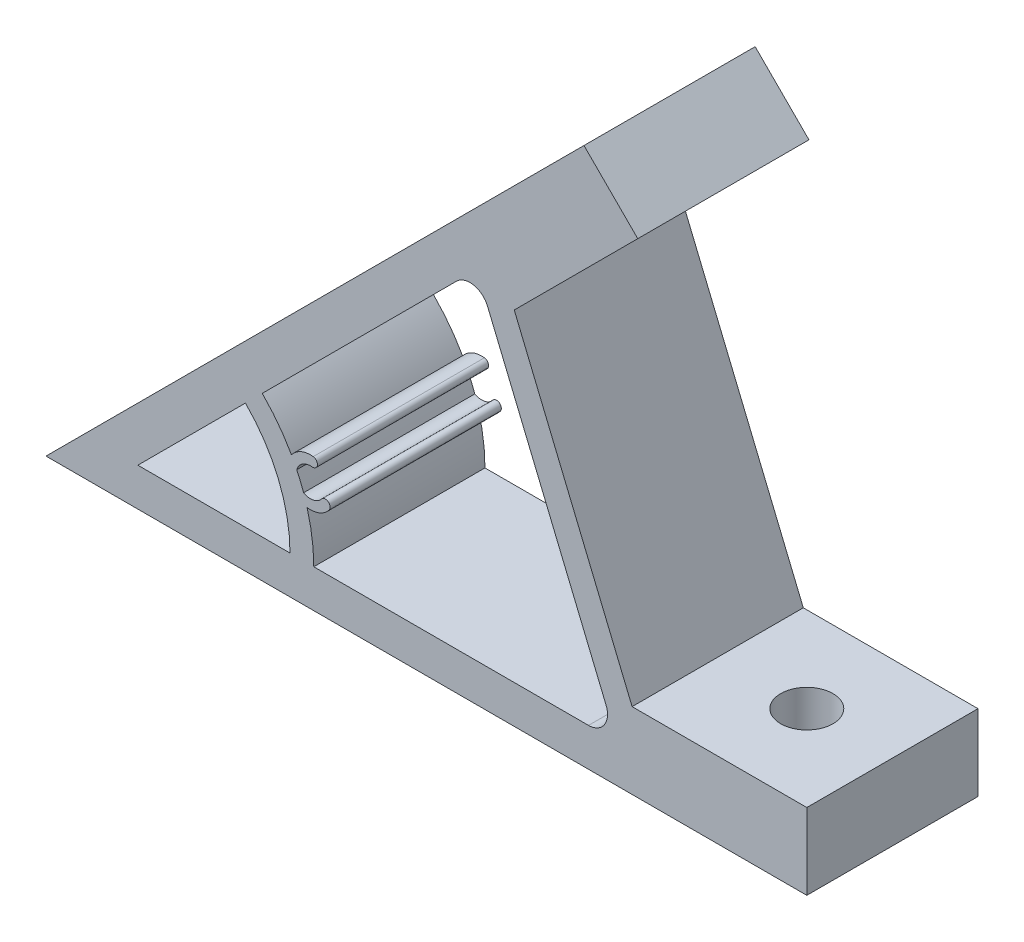
SolidWorks part; units mm, degrees
ref_plane "前视基准面" through (0, 0, 0) normal (0, 0, 1) x (1, 0, 0)
ref_plane "上视基准面" through (0, 0, 0) normal (0, 1, 0) x (1, 0, 0)
ref_plane "右视基准面" through (0, 0, 0) normal (1, 0, 0) x (0, 0, -1)
sketch "草图1" plane through (0, 0, 0) normal (0, 0, 1) x (1, 0, 0)
  line L0 (0, 0) -> (97.3951, 0) construction
  line L1 (0, 0) -> (65.6523, 65.6523) construction
  line L2 (0, 0) -> (80, 0)
  line L3 (0, 0) -> (56.5685, 56.5685)
  line L4 (80, 0) -> (80, 8)
  line L5 (49.2357, 37.922) -> (61.6298, 8)
  line L6 (56.5685, 56.5685) -> (62.2254, 50.9117)
  line L7 (62.2254, 50.9117) -> (49.2357, 37.922)
  line L8 (58.894, 6.7654) -> (46.4282, 36.8605)
  line L9 (43.1662, 37.5094) -> (9.6569, 4)
  line L10 (9.6569, 4) -> (57.0463, 4)
  line L11 (0, 0) -> (69.2985, 28.7044) construction
  line L12 (80, 8) -> (61.6298, 8)
  arc A0 (57.0463, 4) -> (58.894, 6.7654) centre (57.0463, 6) ccw
  arc A1 (46.4282, 36.8605) -> (43.1662, 37.5094) centre (44.5805, 36.0952) ccw
  arc A2 (22.7383, 17.0815) -> (25.8088, 13.0202) centre (9.6569, 4) cw
  arc A3 (20.9706, 15.3137) -> (25.6569, 4) centre (9.6569, 4) cw
  arc A4 (27.086, 10.2029) -> (28.9845, 10.5885) centre (27.8072, 11.5181) ccw
  arc A5 (27.4563, 9.0429) -> (29.7693, 9.9688) centre (27.8072, 11.5181) ccw
  arc A6 (28.0991, 14.001) -> (27.9823, 13.0079) centre (28.0407, 13.5045) cw
  arc A7 (29.7693, 9.9688) -> (28.9845, 10.5885) centre (29.3769, 10.2787) ccw
  arc A8 (27.9823, 13.0079) -> (26.3672, 11.9381) centre (27.8072, 11.5181) ccw
  arc A9 (28.0991, 14.001) -> (25.8088, 13.0202) centre (27.8072, 11.5181) ccw
  arc A10 (26.3672, 11.9381) -> (27.086, 10.2029) centre (9.6569, 4) cw
  arc A11 (27.4563, 9.0429) -> (28.1569, 4) centre (9.6569, 4) cw
  point P8 (40, 0)
  dimension "D6" = 4
  dimension "D10" = 2
  dimension "D12" = 16
  dimension "D13" = 2.5
  dimension "D14" = 3
  dimension "D15" = 5
  dimension "D16" = 19.6458
  dimension "D1" = 45
  dimension "D2" = 8
  dimension "D3" = 80
  dimension "D4" = 80
  dimension "D5" = 8
  dimension "D7" = 4
  dimension "D8" = 67.5
  dimension "D9" = 3
  dimension "D11" = 60
extrude "凸台-拉伸1" add sketch "草图1" along normal blind 18 contours L4 L12 L5 L7 L6 L3 L2 A1 L8 A0 L10 L9 | A11 A5 A7 A4 A10 A8 A6 A9 A2 L9 A3 L10
sketch "草图2" plane through (0, 8, 0) normal (0, 1, 0) x (1, 0, 0)
  line L0 (80, 0) -> (61.6298, 0) construction
  line L1 (80, -18) -> (80, 0) construction
  circle A0 centre (71, -9) radius 2.75
  dimension "D1" = 5.5
  dimension "D2" = 9
  dimension "D3" = 9
extrude "切除-拉伸1" cut sketch "草图2" against normal blind 28
sketch "草图3" plane through (5.6569, -5.6569, 0) normal (0.7071, -0.7071, 0) x (0, 0, -1)
  line L0 (-18, 80) -> (0, 80) construction
  line L1 (0, 80) -> (0, 61.6298) construction
  circle A0 centre (-9, 71) radius 2.75
  dimension "D1" = 9
  dimension "D2" = 5.5
  dimension "D3" = 9
extrude "切除-拉伸2" cut sketch "草图3" against normal blind 28
